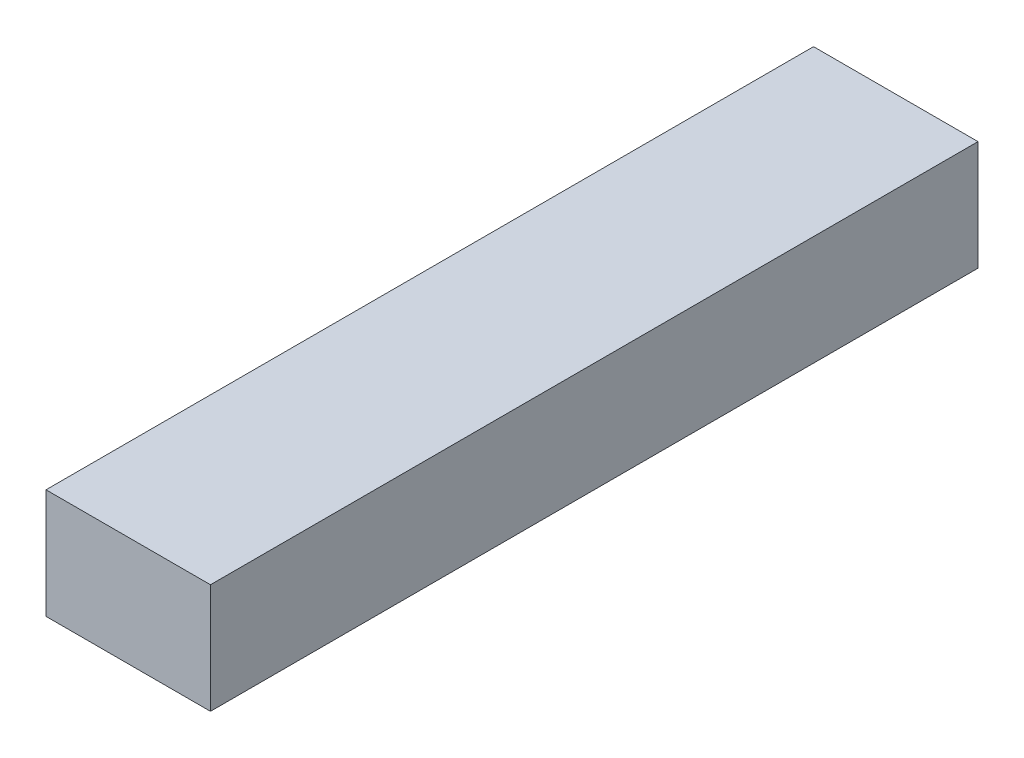
SolidWorks part; units mm, degrees
material "Oak"
ref_plane "Front Plane" through (0, 0, 0) normal (0, 0, 1) x (1, 0, 0)
ref_plane "Top Plane" through (0, 0, 0) normal (0, 1, 0) x (1, 0, 0)
ref_plane "Right Plane" through (0, 0, 0) normal (1, 0, 0) x (0, 0, -1)
sketch "Sketch1" plane through (0, 0, 0) normal (0, 1, 0) x (1, 0, 0)
  line L1 (0, 0) -> (7.5, 0)
  line L2 (0, 0) -> (0, 35)
  line L3 (0, 35) -> (7.5, 35)
  line L4 (7.5, 0) -> (7.5, 35)
  dimension "D1" = 7.5
  dimension "D2" = 35
extrude "Boss-Extrude1" add sketch "Sketch1" along normal blind 5
